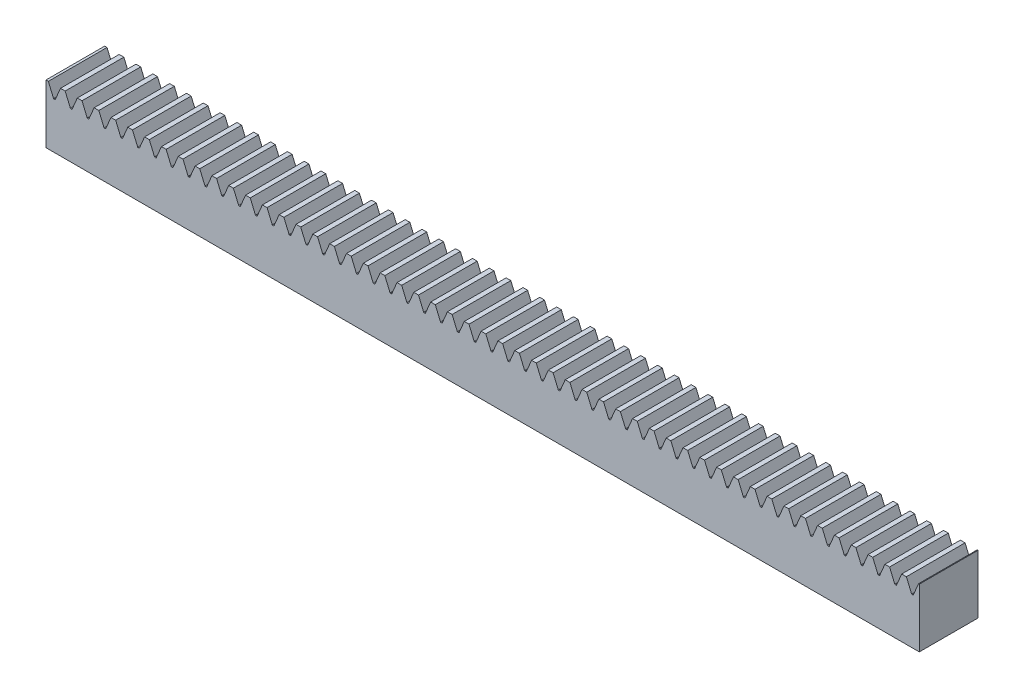
SolidWorks part; units mm, degrees
ref_plane "Front Plane" through (0, 0, 0) normal (0, 0, 1) x (1, 0, 0)
ref_plane "Top Plane" through (0, 0, 0) normal (0, 1, 0) x (1, 0, 0)
ref_plane "Right Plane" through (0, 0, 0) normal (1, 0, 0) x (0, 0, -1)
sketch "Sketch1" plane through (0, 0, 0) normal (1, 0, 0) x (0, 0, -1)
  line L1 (0, 0) -> (19.05, 0)
  line L2 (0, 0) -> (0, -19.05)
  line L3 (0, -19.05) -> (19.05, -19.05)
  line L4 (19.05, 0) -> (19.05, -19.05)
  dimension "D1" = 19.05
  dimension "D2" = 19.05
extrude "Boss-Extrude1" add sketch "Sketch1" along normal blind 283.464
sketch "Sketch2" plane through (0, 0, 0) normal (0, 0, 1) x (1, 0, 0)
  line L0 (0.762, 0) -> (4.699, 0)
  line L1 (283.464, 0) -> (0, 0) construction
  line L2 (4.699, 0) -> (2.9845, -4.064)
  line L3 (2.9845, -4.064) -> (2.4765, -4.064)
  line L4 (2.4765, -4.064) -> (0.762, 0)
  line L5 (2.7305, 0) -> (2.7305, -5.0998) construction
  line L6 (0, 0) -> (0, -19.05) construction
  point P8 (0, 0)
  dimension "D1" = 3.937
  dimension "D2" = 0.508
  dimension "D3" = 4.064
  dimension "D4" = 0.762
extrude "Cut-Extrude1" cut sketch "Sketch2" against normal through all
fillet "Fillet1" radius 0.127 2 edges at (2.9845, -4.064, -9.525) (2.4765, -4.064, -9.525)
pattern_linear "LPattern1" count 52 spacing 5.461 along (1, 0, 0) of "Fillet1", "Cut-Extrude1"
